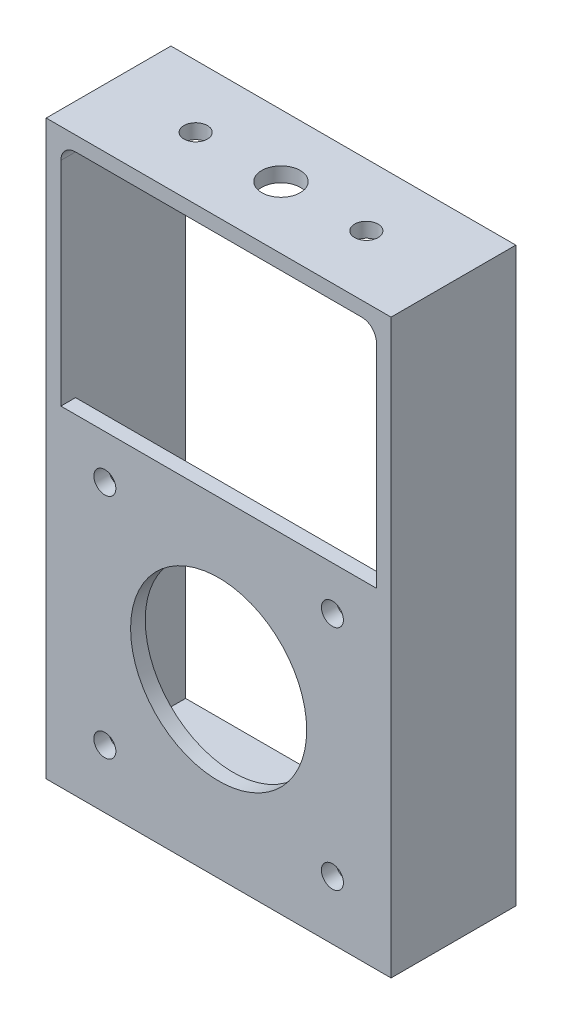
SolidWorks part; units mm, degrees
ref_plane "Front Plane" through (0, 0, 0) normal (0, 0, 1) x (1, 0, 0)
ref_plane "Top Plane" through (0, 0, 0) normal (0, 1, 0) x (1, 0, 0)
ref_plane "Right Plane" through (0, 0, 0) normal (1, 0, 0) x (0, 0, -1)
sketch "Sketch1" plane through (0, 0, 0) normal (0, 0, 1) x (1, 0, 0)
  line L1 (33.5765, 33.5975) -> (76.5765, 33.5975)
  line L2 (33.5765, 33.5975) -> (33.5765, -40.4025)
  line L3 (33.5765, -40.4025) -> (76.5765, -40.4025)
  line L4 (76.5765, 33.5975) -> (76.5765, -40.4025)
  dimension "D1" = 74
  dimension "D2" = 43
extrude "Extrude-Thin1" add sketch "Sketch1" along normal blind 15 thin thin type one direction wall 2
sketch "Sketch6" plane through (0, 0, 15) normal (0, 0, 1) x (1, 0, 0)
  line L1 (31.5765, 35.5975) -> (78.5765, 35.5975)
  line L2 (31.5765, 35.5975) -> (31.5765, -42.4025)
  line L3 (31.5765, -42.4025) -> (78.5765, -42.4025)
  line L4 (78.5765, 35.5975) -> (78.5765, -42.4025)
extrude "Boss-Extrude1" add sketch "Sketch6" along normal blind 2
sketch "Sketch8" plane through (0, 0, 15) normal (0, 0, -1) x (-1, 0, 0)
  line L0 (-33.5765, 33.5975) -> (-33.5765, -40.4025) construction
  line L1 (-76.5765, 33.5975) -> (-33.5765, 33.5975)
  line L2 (-76.5765, 33.5975) -> (-76.5765, 2.5975)
  line L3 (-76.5765, 2.5975) -> (-33.5765, 2.5975)
  line L4 (-33.5765, 33.5975) -> (-33.5765, 2.5975)
  line L5 (-33.5765, -40.4025) -> (-76.5765, -40.4025) construction
  dimension "D1" = 43
extrude "Cut-Extrude1" cut sketch "Sketch8" against normal blind 10
sketch "Sketch9" plane through (0, 0, 15) normal (0, 0, -1) x (-1, 0, 0)
  line L0 (-33.5765, 2.5975) -> (-76.5765, -40.4025)
  circle A0 centre (-55.0765, -18.9025) radius 12
  dimension "D1" = 24
extrude "Cut-Extrude2" cut sketch "Sketch9" against normal blind 10 contours L0 A0 | L0 A0
sketch "Sketch11" plane through (0, 0, 15) normal (0, 0, -1) x (-1, 0, 0)
  line L0 (-33.5765, 2.5975) -> (-76.5765, -40.4025)
  circle A0 centre (-39.5697, -3.3957) radius 1.5
  dimension "D1" = 3
  dimension "D2" = 21.93
extrude "Cut-Extrude3" cut sketch "Sketch11" against normal blind 10 contours L0 A0 | L0 A0
pattern_circular "CirPattern1" count 4 over 360 about axis through (55.0765, -18.9025, 0) along (0, 0, 1) of "Cut-Extrude3"
sketch "Sketch12" plane through (0, 35.5975, 0) normal (0, 1, 0) x (1, 0, 0)
  line L0 (55.0765, -17) -> (55.0765, 0)
  line L1 (78.5765, -17) -> (31.5765, -17) construction
  line L2 (78.5765, 0) -> (31.5765, 0) construction
  circle A0 centre (55.0765, -8.5) radius 2.625
  circle A1 centre (43.4465, -8.5) radius 1.6
  circle A2 centre (66.7065, -8.5) radius 1.6
  dimension "D1" = 5.25
  dimension "D2" = 3.2
  dimension "D3" = 11.63
  dimension "D4" = 3.2
  dimension "D5" = 11.63
extrude "Cut-Extrude4" cut sketch "Sketch12" against normal blind 10 contours L0 A0 | L0 A0 | A1 | A2
fillet "Fillet1" radius 2 2 edges at (33.5765, 33.5975, 8.5) (76.5765, 33.5975, 8.5)
